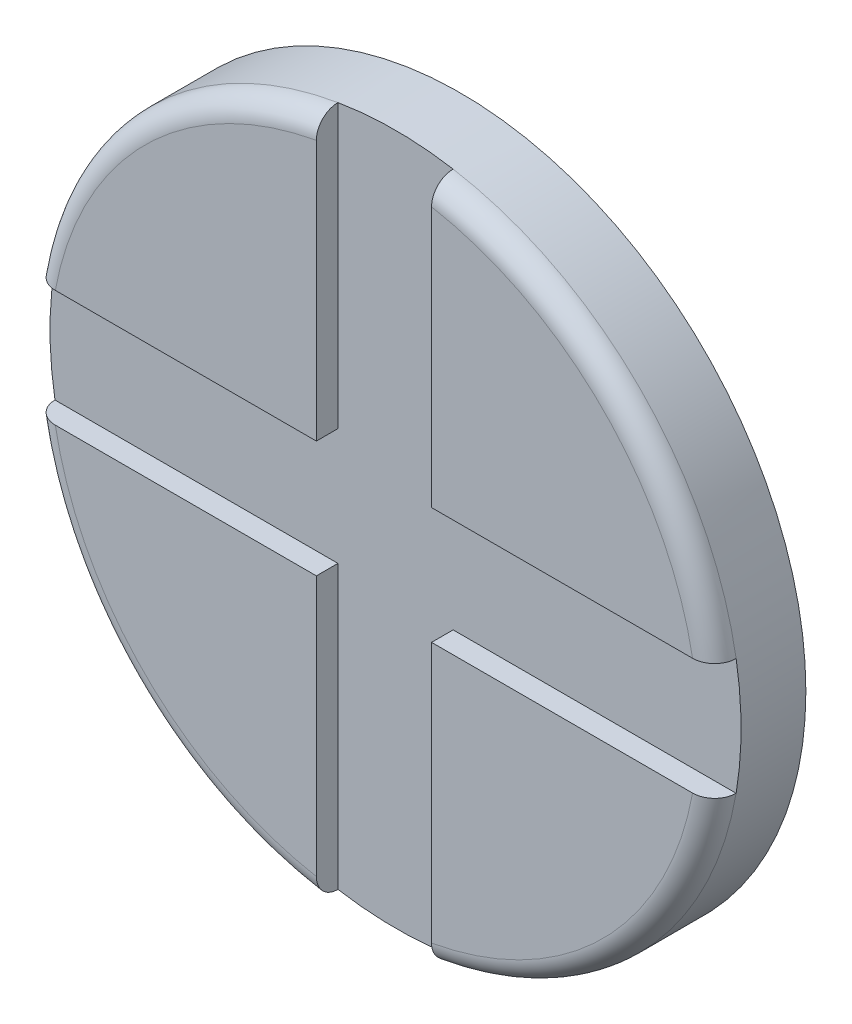
SolidWorks part; units mm, degrees
material "Alloy Steel"
ref_plane "Front Plane" through (0, 0, 0) normal (0, 0, 1) x (1, 0, 0)
ref_plane "Top Plane" through (0, 0, 0) normal (0, 1, 0) x (1, 0, 0)
ref_plane "Right Plane" through (0, 0, 0) normal (1, 0, 0) x (0, 0, -1)
sketch "Sketch1" plane through (0, 0, 0) normal (0, 0, 1) x (1, 0, 0)
  circle A0 centre (0, 0) radius 4
extrude "Boss-Extrude1" add sketch "Sketch1" along normal blind 1
sketch "Sketch2" plane through (0, 0, 1) normal (0, 0, 1) x (1, 0, 0)
  line L0 (0, 0) -> (4, 0) construction
  line L1 (4, 0) -> (-8.1063, 0) construction
  line L2 (-8.1063, 0.6755) -> (-0.6667, 0.6755)
  line L3 (-0.6667, 0.6755) -> (-0.6667, 8.466)
  line L4 (-0.6667, 8.466) -> (0.6667, 8.466)
  line L5 (-8.1063, 0.6755) -> (-8.1063, -0.6755)
  line L6 (0, 0) -> (0, 9.1327) construction
  line L7 (0, 9.1327) -> (0, -8.7116) construction
  line L8 (-8.1063, -0.6755) -> (-0.6667, -0.6755)
  line L9 (-0.6667, -8.466) -> (0.6667, -8.466)
  line L10 (-0.6667, -0.6755) -> (-0.6667, -8.466)
  line L11 (0.6667, -0.6755) -> (0.6667, -8.466)
  line L12 (8.1063, -0.6755) -> (0.6667, -0.6755)
  line L13 (8.1063, 0.6755) -> (8.1063, -0.6755)
  line L14 (8.1063, 0.6755) -> (0.6667, 0.6755)
  line L15 (0.6667, 0.6755) -> (0.6667, 8.466)
  circle A0 centre (0, 0) radius 4 construction
  point P18 (0, -8.466)
  point P23 (0, 8.466)
extrude "Cut-Extrude1" cut sketch "Sketch2" against normal blind 0.25
fillet "Fillet1" radius 0.25 4 edges at (2.8253, 2.8316, 1) (2.8253, -2.8316, 1) (-2.8253, -2.8316, 1) (-2.8253, 2.8316, 1)
